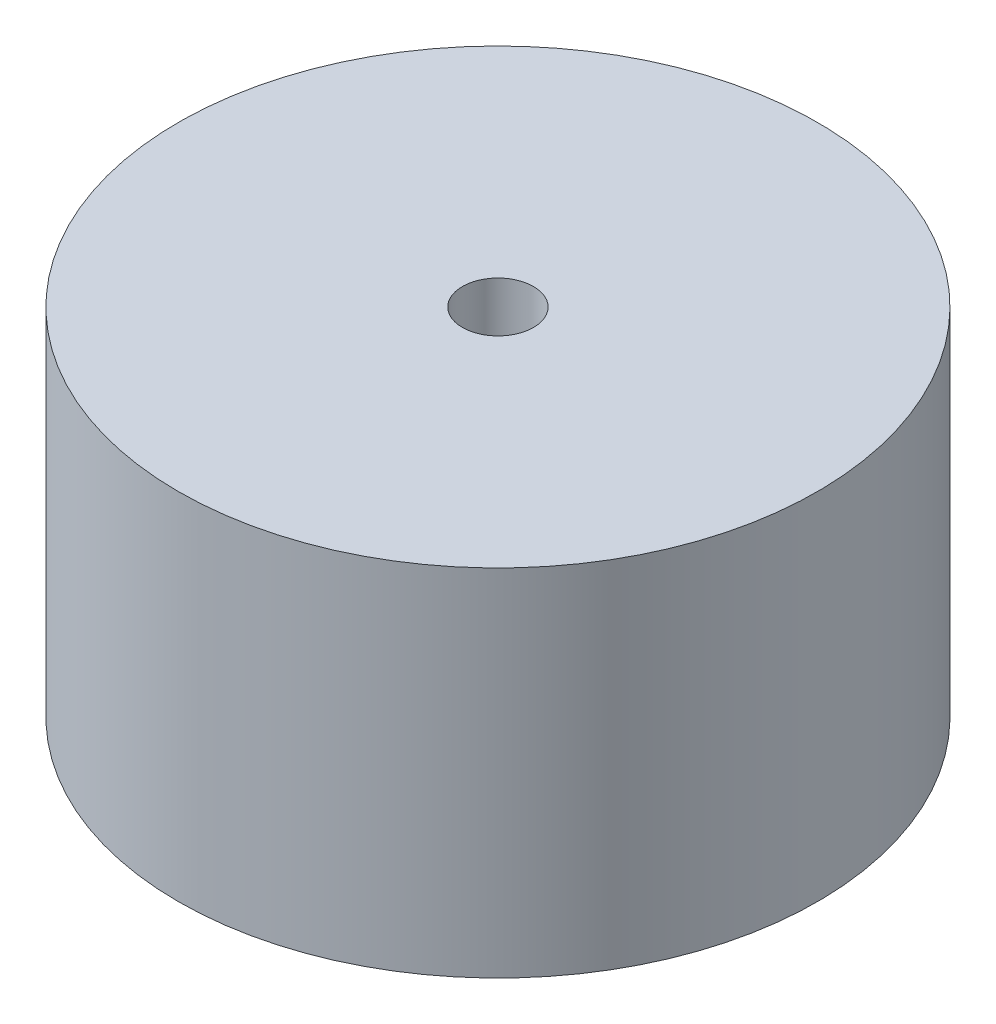
SolidWorks part; units mm, degrees
ref_plane "Front Plane" through (0, 0, 0) normal (0, 0, 1) x (1, 0, 0)
ref_plane "Top Plane" through (0, 0, 0) normal (0, 1, 0) x (1, 0, 0)
ref_plane "Right Plane" through (0, 0, 0) normal (1, 0, 0) x (0, 0, -1)
sketch "Sketch1" plane through (0, 0, 0) normal (0, 1, 0) x (1, 0, 0)
  circle A0 centre (0, 0) radius 0.5
  circle A1 centre (0, 0) radius 4 construction
  circle A2 centre (0, 0) radius 4.5
  circle A3 centre (0, 0) radius 5 construction
  dimension "D1" = 9
  dimension "D2" = 0.5
  dimension "D3" = 0.5
  dimension "D4" = 1
extrude "Boss-Extrude1" add sketch "Sketch1" along normal blind 5
